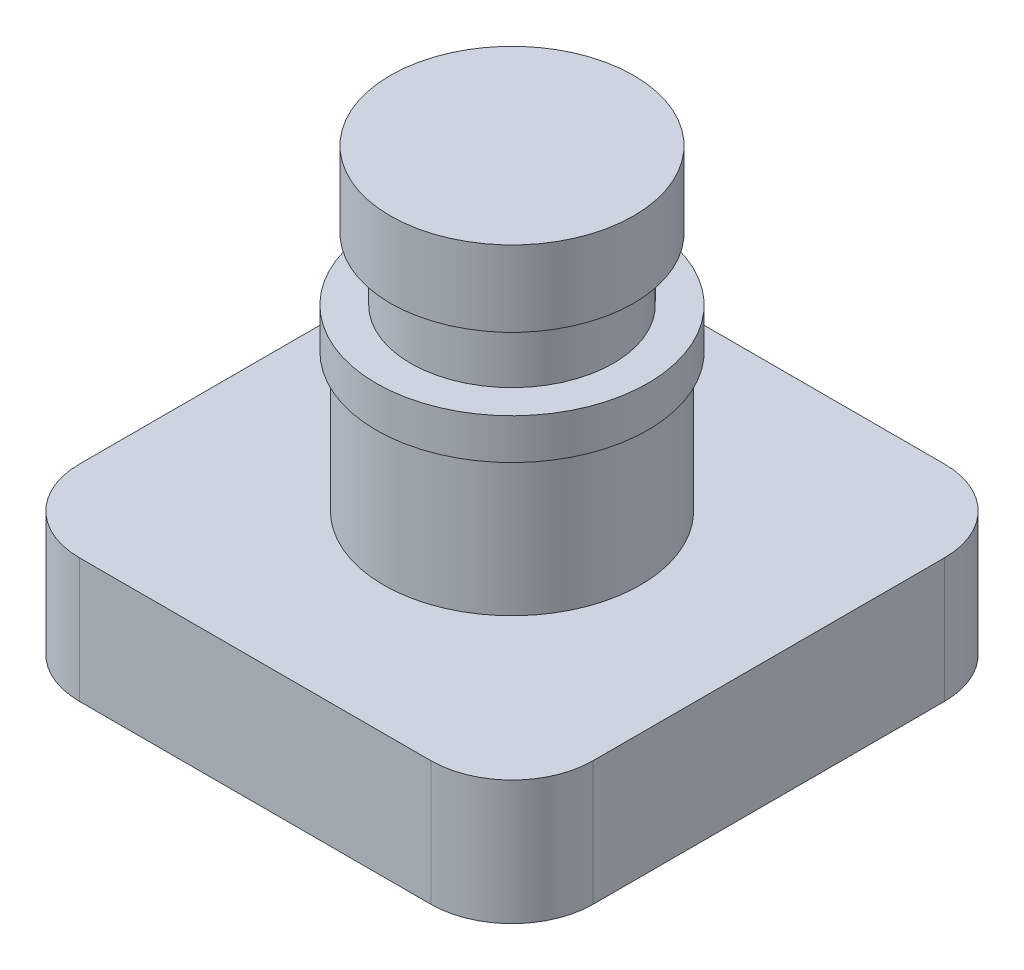
SolidWorks part; units mm, degrees
ref_plane "Alzado" through (0, 0, 0) normal (0, 0, 1) x (1, 0, 0)
ref_plane "Planta" through (0, 0, 0) normal (0, 1, 0) x (1, 0, 0)
ref_plane "Vista lateral" through (0, 0, 0) normal (1, 0, 0) x (0, 0, -1)
sketch "Croquis1" plane through (0, 0, 0) normal (0, 1, 0) x (1, 0, 0)
  line L1 (-6.5, 9.5) -> (6.5, 9.5)
  line L2 (-9.5, 6.5) -> (-9.5, -6.5)
  line L3 (-6.5, -9.5) -> (6.5, -9.5)
  line L4 (9.5, 6.5) -> (9.5, -6.5)
  line L5 (-9.5, 9.5) -> (9.5, -9.5) construction
  line L6 (-9.5, -9.5) -> (9.5, 9.5) construction
  line L7 (-4.25, 4.75) -> (4.25, 4.75)
  line L8 (-4.75, 4.25) -> (-4.75, -4.25)
  line L9 (-4.25, -4.75) -> (4.25, -4.75)
  line L10 (4.75, 4.25) -> (4.75, -4.25)
  line L11 (-4.75, 4.75) -> (4.75, -4.75) construction
  line L12 (-4.75, -4.75) -> (4.75, 4.75) construction
  arc A0 (-6.5, 9.5) -> (-9.5, 6.5) centre (-6.5, 6.5) ccw
  arc A1 (-9.5, -6.5) -> (-6.5, -9.5) centre (-6.5, -6.5) ccw
  arc A2 (6.5, -9.5) -> (9.5, -6.5) centre (6.5, -6.5) ccw
  arc A3 (6.5, 9.5) -> (9.5, 6.5) centre (6.5, 6.5) cw
  arc A4 (4.25, 4.75) -> (4.75, 4.25) centre (4.25, 4.25) cw
  arc A5 (-4.25, 4.75) -> (-4.75, 4.25) centre (-4.25, 4.25) ccw
  arc A6 (-4.75, -4.25) -> (-4.25, -4.75) centre (-4.25, -4.25) ccw
  arc A7 (4.25, -4.75) -> (4.75, -4.25) centre (4.25, -4.25) ccw
  circle A8 centre (0, 0) radius 4.75
  point P0 (0, 0)
  point P18 (0, 0)
  dimension "D3" = 3
  dimension "D4" = 3
  dimension "D5" = 3
  dimension "D6" = 3
  dimension "D9" = 0.5
  dimension "D10" = 0.5
  dimension "D11" = 0.5
  dimension "D12" = 0.5
  dimension "D13" = 9.5
  dimension "D1" = 19
  dimension "D2" = 19
  dimension "D7" = 9.5
  dimension "D8" = 9.5
extrude "Saliente-Extruir2" add sketch "Croquis1" along normal blind 4.6 contours A3 L1 A0 L2 A1 L3 A2 L4 A7 L9 A6 L8 A5 L7 A4 L10 | A8 L8 A6 L9 | A8 L9 A7 L10 | A8 L10 A4 L7 | A8 L7 A5 L8
sketch "Croquis2" plane through (0, 4.6, 0) normal (0, 1, 0) x (1, 0, 0)
  circle A0 centre (0, 0) radius 4.75 construction
  circle A1 centre (0, 0) radius 4.75
extrude "Saliente-Extruir3" add sketch "Croquis2" along normal blind 5.1 and the other way up to surface (4.6 mm away) other way up to face at (0, 0, 4.75)
sketch "Croquis3" plane through (0, 0, 0) normal (0, 1, 0) x (1, 0, 0)
  point P0 (0, 0)
sketch3d "Croquis3D1"
  point P0 (2.034, 9.7, -0.0531)
sketch3d "Croquis3D2"
  point P0 (1.7762, 9.7, 0.5663)
ref_plane "Plano2" through (0, 9.7, 0) normal (0, 1, 0) x (1, 0, 0)
sketch "Croquis4" plane through (0, 9.7, 0) normal (0, 1, 0) x (1, 0, 0)
  circle A0 centre (0, 0) radius 5.025
  dimension "D1" = 10.05
extrude "Saliente-Extruir4" add sketch "Croquis4" along normal blind 1.5
sketch3d "Croquis3D3"
  point P0 (2.7465, 11.2, -1.3412)
sketch3d "Croquis3D4"
  point P0 (1.3175, 11.2, -1.0683)
ref_plane "Plano4" through (0, 11.2, 0) normal (0, 1, 0) x (1, 0, 0)
sketch "Croquis6" plane through (0, 11.2, 0) normal (0, 1, 0) x (1, 0, 0)
  circle A0 centre (0, 0) radius 3.75
  dimension "D1" = 7.5
extrude "Saliente-Extruir5" add sketch "Croquis6" along normal blind 2.3 contours A0
sketch3d "Croquis3D5"
  point P0 (-1.6927, 13.5, -0.5575)
sketch3d "Croquis3D6"
  point P0 (2.0249, 13.5, -0.4347)
ref_plane "Plano6" through (0, 13.5, 0) normal (0, 1, 0) x (1, 0, 0)
sketch "Croquis7" plane through (0, 13.5, 0) normal (0, 1, 0) x (1, 0, 0)
  circle A0 centre (0, 0) radius 4.5
  dimension "D1" = 9
extrude "Saliente-Extruir6" add sketch "Croquis7" along normal blind 2.8 contours A0
